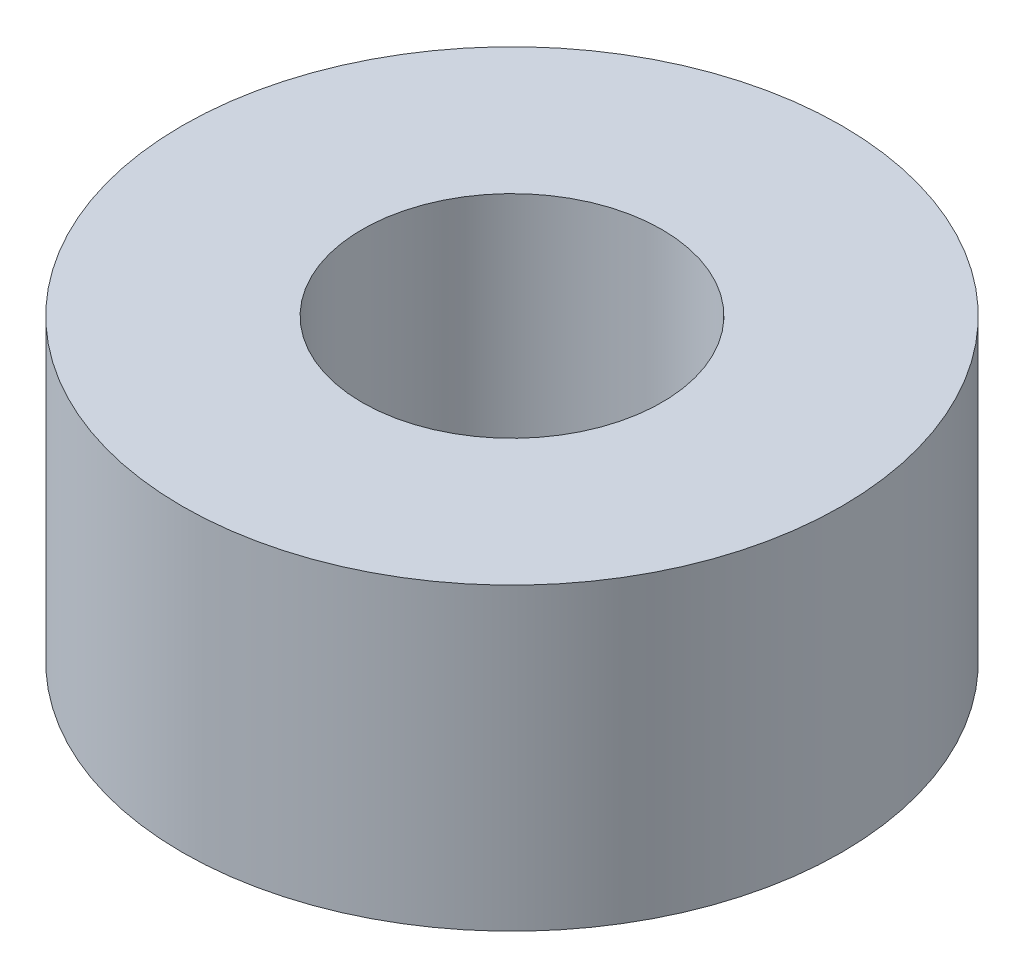
SolidWorks part; units mm, degrees
ref_plane "Front Plane" through (0, 0, 0) normal (0, 0, 1) x (1, 0, 0)
ref_plane "Top Plane" through (0, 0, 0) normal (0, 1, 0) x (1, 0, 0)
ref_plane "Right Plane" through (0, 0, 0) normal (1, 0, 0) x (0, 0, -1)
sketch "Sketch1" plane through (0, 0, 0) normal (0, 1, 0) x (1, 0, 0)
  circle A0 centre (0, 0) radius 5.5
  circle A1 centre (0, 0) radius 2.5
  dimension "D1" = 5
  dimension "D2" = 11
extrude "Boss-Extrude1" add sketch "Sketch1" along normal blind 5 contours A1
